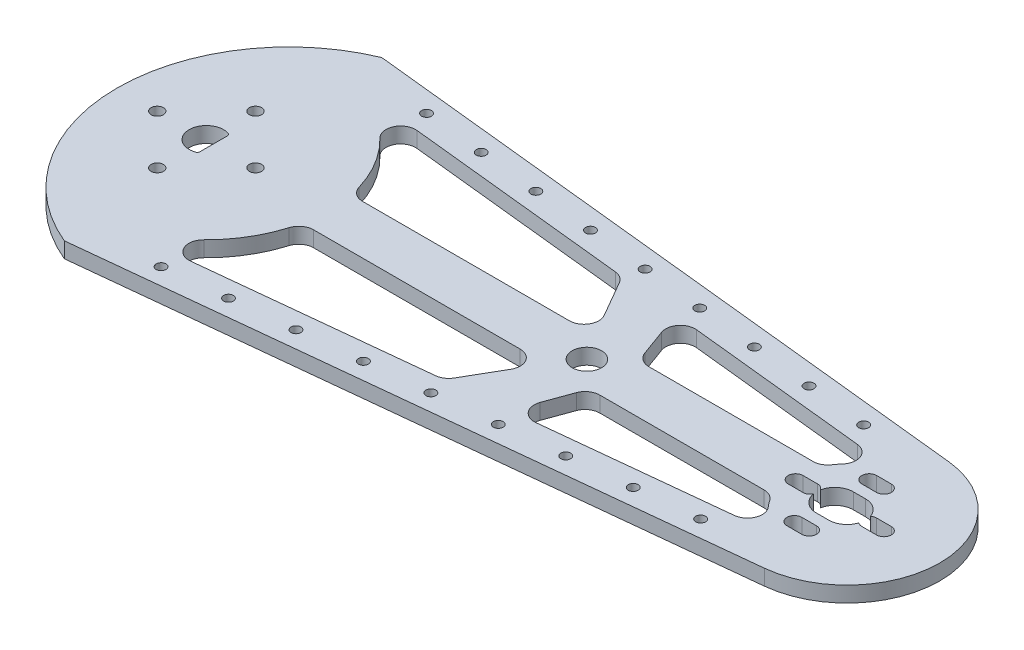
SolidWorks part; units mm, degrees
ref_plane "Alzado" through (0, 0, 0) normal (0, 0, 1) x (1, 0, 0)
ref_plane "Planta" through (0, 0, 0) normal (0, 1, 0) x (1, 0, 0)
ref_plane "Vista lateral" through (0, 0, 0) normal (1, 0, 0) x (0, 0, -1)
sketch "Sketch1" plane through (0, 0, 0) normal (0, 1, 0) x (1, 0, 0)
  line L0 (0, 0) -> (261, 0) construction
  line L1 (6.7879, 64.6446) -> (264.9416, 37.5378)
  line L2 (264.9416, -37.5378) -> (6.7879, -64.6446)
  line L3 (7.6042, 72.4195) -> (265.7579, 45.3126) construction
  line L4 (265.7579, -45.3126) -> (7.6042, -72.4195) construction
  arc A0 (6.7879, 64.6446) -> (6.7879, -64.6446) centre (0, 0) ccw
  arc A1 (264.9416, -37.5378) -> (264.9416, 37.5378) centre (261, 0) ccw
  circle A2 centre (0, 0) radius 72.8176 construction
  circle A3 centre (261, 0) radius 45.5618 construction
  dimension "D1" = 130
  dimension "D4" = 145.6352
  dimension "D5" = 91.1235
  dimension "D2" = 261
extrude "Boss-Extrude1" add sketch "Sketch1" along normal blind 6.35
sketch "Sketch2" plane through (0, 6.35, 0) normal (0, 1, 0) x (1, 0, 0)
  line L0 (130.018, 36.6226) -> (39.673, 46.1091)
  line L1 (170.2658, 10) -> (237.1206, 10)
  line L2 (131.5636, 36.4603) -> (141.081, 35.461) construction
  line L3 (48.9898, 10) -> (240.5722, 10) construction
  line L5 (170.2658, -10) -> (237.1206, -10)
  line L8 (164.6276, -13.9479) -> (160.7057, -24.7232)
  line L9 (240.1393, -25.0596) -> (166.9705, -32.7425)
  line L10 (121.3251, -74.4444) -> (136.5752, -32.5453) construction
  line L11 (131.5636, -36.4603) -> (141.081, -35.461) construction
  line L12 (110.4908, -69.3923) -> (135.2583, -26.4938) construction
  line L13 (130.018, -36.6226) -> (39.673, -46.1091)
  line L14 (134.5876, -33.6554) -> (143.0489, -19)
  line L15 (263.3751, 22.6198) -> (5.2214, 49.7266)
  line L16 (240.1393, 25.0596) -> (166.9705, 32.7425)
  line L17 (0, 0) -> (261, 0) construction
  line L18 (53.6656, -10) -> (137.8528, -10)
  line L21 (53.6656, 10) -> (137.8528, 10)
  line L22 (110.4908, 69.3923) -> (135.2583, 26.4938) construction
  line L23 (121.3251, 74.4444) -> (136.5752, 32.5453) construction
  line L24 (134.5876, 33.6554) -> (143.0489, 19)
  line L25 (164.6276, 13.9479) -> (160.7057, 24.7232)
  arc A0 (237.1206, 10) -> (242.1052, 12.6602) centre (237.1206, 16) ccw
  arc A1 (240.1393, 25.0596) -> (243.9979, 15.1071) centre (239.5127, 19.0924) cw
  arc A11 (39.673, 46.1091) -> (34.8629, 35.841) centre (39.0465, 40.1419) ccw
  arc A12 (243.9979, 15.1071) -> (242.1052, 12.6602) centre (261, 0) ccw
  arc A13 (47.9157, 14.2857) -> (34.8629, 35.841) centre (0, 0) ccw
  arc A14 (160.7057, 24.7232) -> (166.9705, 32.7425) centre (166.3439, 26.7753) cw
  arc A15 (164.6276, 13.9479) -> (170.2658, 10) centre (170.2658, 16) ccw
  arc A16 (136.5752, 32.5453) -> (131.5636, 36.4603) centre (130.937, 30.4932) ccw construction
  arc A17 (135.2583, 26.4938) -> (141.081, 35.461) centre (140.4544, 29.4938) cw construction
  arc A18 (110.4908, 69.3923) -> (121.3251, 74.4444) centre (115.687, 72.3923) ccw construction
  arc A19 (143.0489, 19) -> (137.8528, 10) centre (137.8528, 16) cw
  arc A20 (134.5876, 33.6554) -> (130.018, 36.6226) centre (129.3915, 30.6554) ccw
  arc A21 (53.6656, 10) -> (47.9157, 14.2857) centre (53.6656, 16) cw
  arc A22 (243.9979, -15.1071) -> (242.1052, -12.6602) centre (261, 0) cw
  arc A23 (237.1206, -10) -> (242.1052, -12.6602) centre (237.1206, -16) cw
  arc A24 (164.6276, -13.9479) -> (170.2658, -10) centre (170.2658, -16) cw
  arc A25 (240.1393, -25.0596) -> (243.9979, -15.1071) centre (239.5127, -19.0924) ccw
  arc A26 (160.7057, -24.7232) -> (166.9705, -32.7425) centre (166.3439, -26.7753) ccw
  arc A27 (136.5752, -32.5453) -> (131.5636, -36.4603) centre (130.937, -30.4932) cw construction
  arc A28 (135.2583, -26.4938) -> (141.081, -35.461) centre (140.4544, -29.4938) ccw construction
  arc A29 (110.4908, -69.3923) -> (121.3251, -74.4444) centre (115.687, -72.3923) cw construction
  arc A30 (47.9157, -14.2857) -> (34.8629, -35.841) centre (0, 0) cw
  arc A31 (39.673, -46.1091) -> (34.8629, -35.841) centre (39.0465, -40.1419) cw
  arc A32 (134.5876, -33.6554) -> (130.018, -36.6226) centre (129.3915, -30.6554) cw
  arc A33 (143.0489, -19) -> (137.8528, -10) centre (137.8528, -16) ccw
  arc A34 (53.6656, -10) -> (47.9157, -14.2857) centre (53.6656, -16) ccw
  arc A35 (6.7879, -64.6446) -> (6.7879, 64.6446) centre (33.6407, 0) cw
  arc A37 (6.7879, 64.6446) -> (6.7879, -64.6446) centre (0, 0) ccw construction
  arc A38 (6.7879, 64.6446) -> (6.7879, -64.6446) centre (0, 0) ccw
  point P31 (166.0645, 10)
  point P34 (135.2927, 36.0688)
  point P39 (144.781, 10)
  point P44 (133.0588, 36.3033)
  dimension "D2" = 15
  dimension "D1" = 50
  dimension "D4" = 6
  dimension "D6" = 60
  dimension "D5" = 6
  dimension "D10" = 70
  dimension "D7" = 110
  dimension "D8" = 20
  dimension "D9" = 3
  dimension "D3" = 20
extrude "Cut-Extrude1" cut sketch "Sketch2" against normal through all
sketch "Sketch3" plane through (0, 6.35, 0) normal (0, 1, 0) x (1, 0, 0)
  line L1 (3, 5.6569) -> (3, -5.6569)
  circle A1 centre (261, 0) radius 7.5
  arc A4 (2.3333, 6.5997) -> (2.3333, -6.5997) centre (0, 0) ccw
  arc A5 (3, -5.6569) -> (2.3333, -6.5997) centre (2, -5.6569) cw
  arc A6 (3, 5.6569) -> (2.3333, 6.5997) centre (2, 5.6569) ccw
  circle A7 centre (0, 0) radius 7 construction
  dimension "D1" = 14
  dimension "D3" = 15
  dimension "D4" = 1
  dimension "D2" = 10
  dimension "D5" = 4
extrude "Cut-Extrude2" cut sketch "Sketch3" against normal through all
sketch "Sketch4" plane through (0, 6.35, 0) normal (0, 1, 0) x (1, 0, 0)
  circle A0 centre (261, 0) radius 15 construction
  circle A1 centre (0, 0) radius 20 construction
  dimension "D1" = 40
  dimension "D2" = 30
hole_wizard "M6x1.0 Tapped Hole1" positions "Sketch5" profile "Sketch6" tap size "M6x1.0" standard "ANSI Metric" end condition through all
sketch "Sketch5" plane through (0, 6.35, 0) normal (0, 1, 0) x (1, 0, 0)
  circle A0 centre (0, 0) radius 20 construction
  circle A1 centre (261, 0) radius 15 construction
  point P0 (0, 20)
  point P4 (20, 0)
  point P6 (0, -20)
  point P8 (-20, 0)
  point P10 (276, 0)
  point P14 (246, 0.0372)
  point P16 (276, 0)
  point P22 (246, 0)
  point P24 (260.5103, 14.992)
  point P26 (260.5103, -14.992)
cosmetic thread "Hole Thread5"
cosmetic thread "Hole Thread6"
cosmetic thread "Hole Thread7"
cosmetic thread "Hole Thread8"
sketch "Sketch6" plane through (0, 6.35, -20) normal (1, 0, 0) x (0, 0, 1)
  line L0 (0, 0) -> (0, 6.35)
  line L1 (0, 6.35) -> (2.5, 6.35)
  line L2 (2.5, 6.35) -> (2.5, 0)
  line L5 (2.5, 0) -> (0, 0)
  line L11 (0, -6.35) -> (0, 107.95) construction
  dimension "Thru Tap Drill Dia." = 5
  dimension "Thru Tap Drill Depth" = 6.35
cosmetic thread "Hole Thread9"
cosmetic thread "Hole Thread10"
cosmetic thread "Hole Thread11"
cosmetic thread "Hole Thread12"
cosmetic thread "Hole Thread13"
cosmetic thread "Hole Thread14"
sketch "Sketch7" plane through (0, 6.35, 0) normal (0, 1, 0) x (1, 0, 0)
  line L0 (261, 0) -> (256, 0) construction
  line L1 (261, -7.5) -> (256, -7.5)
  line L2 (261, 7.5) -> (256, 7.5)
  line L3 (246, 0) -> (240, 0) construction
  line L4 (246, -3) -> (240, -3)
  line L5 (246, 3) -> (240, 3)
  line L6 (260.5103, -14.992) -> (254.5103, -14.992) construction
  line L7 (260.5103, -17.992) -> (254.5103, -17.992)
  line L8 (260.5103, -11.992) -> (254.5103, -11.992)
  line L9 (276, 0) -> (270, 0) construction
  line L10 (276, -3) -> (270, -3)
  line L11 (276, 3) -> (270, 3)
  line L12 (261, 15) -> (255, 15) construction
  line L13 (261, 12) -> (255, 12)
  line L14 (261, 18) -> (255, 18)
  arc A0 (261, -7.5) -> (268.125, -2.3419) centre (261, 0) ccw
  arc A1 (256, 7.5) -> (248.6375, 1.4295) centre (256, 0) ccw
  circle A2 centre (261, 0) radius 15 construction
  arc A3 (246, -3) -> (248.6375, -1.4295) centre (246, 0) ccw
  arc A4 (240, 3) -> (240, -3) centre (240, 0) ccw
  arc A5 (260.5103, -17.992) -> (260.5103, -11.992) centre (260.5103, -14.992) ccw
  arc A6 (254.5103, -11.992) -> (254.5103, -17.992) centre (254.5103, -14.992) ccw
  arc A7 (276, -3) -> (276, 3) centre (276, 0) ccw
  arc A8 (270, 3) -> (268.125, 2.3419) centre (270, 0) ccw
  arc A9 (261, 12) -> (261, 18) centre (261, 15) ccw
  arc A10 (255, 18) -> (255, 12) centre (255, 15) ccw
  arc A11 (248.6375, -1.4295) -> (256, -7.5) centre (256, 0) ccw
  arc A12 (248.6375, 1.4295) -> (246, 3) centre (246, 0) ccw
  arc A13 (268.125, -2.3419) -> (270, -3) centre (270, 0) ccw
  arc A14 (268.125, 2.3419) -> (261, 7.5) centre (261, 0) ccw
  point P13 (243.01, 0)
  point P21 (257.5103, -14.992)
  point P29 (273.01, 0)
  point P36 (258, 15)
  dimension "D3" = 6
  dimension "D1" = 7.5
  dimension "D11" = 3
  dimension "D2" = 5
  dimension "D4" = 6
  dimension "D5" = 6
  dimension "D6" = 6
  dimension "D7" = 6
  dimension "D8" = 6
  dimension "D9" = 6
  dimension "D10" = 6
extrude "Cut-Extrude4" cut sketch "Sketch7" against normal blind 10
sketch "Sketch8" plane through (0, 6.35, 0) normal (0, 1, 0) x (1, 0, 0)
  line L0 (0, 0) -> (256, 0) construction
  line L3 (35.6283, -54.0751) -> (234.5347, -33.1893) construction
  line L4 (6.7879, -64.6446) -> (264.9416, -37.5378) construction
  line L5 (166.9705, -32.7425) -> (240.1393, -25.0596) construction
  line L6 (135.8647, -51.0912) -> (135.0815, -43.6322) construction
  line L9 (135.8647, 51.0912) -> (135.0815, 43.6322) construction
  circle A13 centre (35.6283, -54.0751) radius 2
  circle A14 centre (60.4916, -51.4643) radius 2
  circle A15 centre (85.3549, -48.8536) radius 2
  circle A16 centre (110.2182, -46.2429) radius 2
  circle A17 centre (135.0815, -43.6322) radius 2
  circle A18 centre (159.9448, -41.0215) radius 2
  circle A19 centre (184.8081, -38.4108) radius 2
  circle A20 centre (209.6714, -35.8) radius 2
  circle A21 centre (234.5347, -33.1893) radius 2
  circle A22 centre (234.5347, 33.1893) radius 2
  circle A23 centre (209.6714, 35.8) radius 2
  circle A24 centre (184.8081, 38.4108) radius 2
  circle A25 centre (159.9448, 41.0215) radius 2
  circle A26 centre (135.0815, 43.6322) radius 2
  circle A27 centre (110.2182, 46.2429) radius 2
  circle A28 centre (85.3549, 48.8536) radius 2
  circle A29 centre (60.4916, 51.4643) radius 2
  circle A30 centre (35.6283, 54.0751) radius 2
  dimension "D1" = 200
  dimension "D2" = 4
  dimension "D3" = 9
extrude "Cut-Extrude5" cut sketch "Sketch8" against normal blind 10
sketch "Sketch9" plane through (0, 6.35, 0) normal (0, 1, 0) x (1, 0, 0)
  circle A0 centre (155, 0) radius 6
  point P0 (155, 0)
  dimension "D1" = 12
  dimension "D3" = 155
extrude "Cut-Extrude6" cut sketch "Sketch9" against normal blind 10
